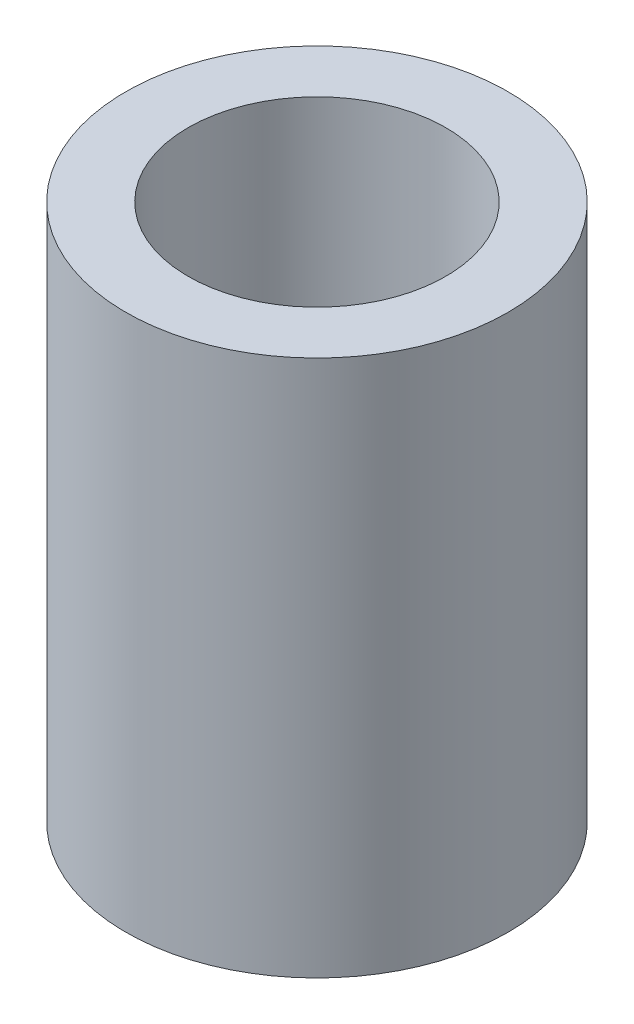
SolidWorks part; units mm, degrees
material "Caucho"
ref_plane "Front" through (0, 0, 0) normal (0, 0, 1) x (1, 0, 0)
ref_plane "Top" through (0, 0, 0) normal (0, 1, 0) x (1, 0, 0)
ref_plane "Right" through (0, 0, 0) normal (1, 0, 0) x (0, 0, -1)
sketch "Croquis1" plane through (0, 0, 0) normal (0, 0, 1) x (1, 0, 0)
  line L0 (0, 0) -> (0, 25)
  line L1 (0, 25) -> (8.9, 25)
  line L2 (8.9, 25) -> (8.9, 0)
  line L3 (8.9, 0) -> (0, 0)
  dimension "D1" = 25
  dimension "8.9" = 8.9
revolve "Revolución1" add sketch "Croquis1" angle 360 about L0
sketch "Croquis2" plane through (0, 25, 0) normal (0, 1, 0) x (1, 0, 0)
  circle A0 centre (0, 0) radius 6
  dimension "D1" = 12
extrude "Cortar-Extruir1" cut sketch "Croquis2" against normal blind 17
sketch "Croquis3" plane through (0, 0, 0) normal (0, -1, 0) x (1, 0, 0)
  circle A0 centre (0, 0) radius 3
  dimension "6" = 6
extrude "Cortar-Extruir2" cut sketch "Croquis3" against normal blind 12.5
